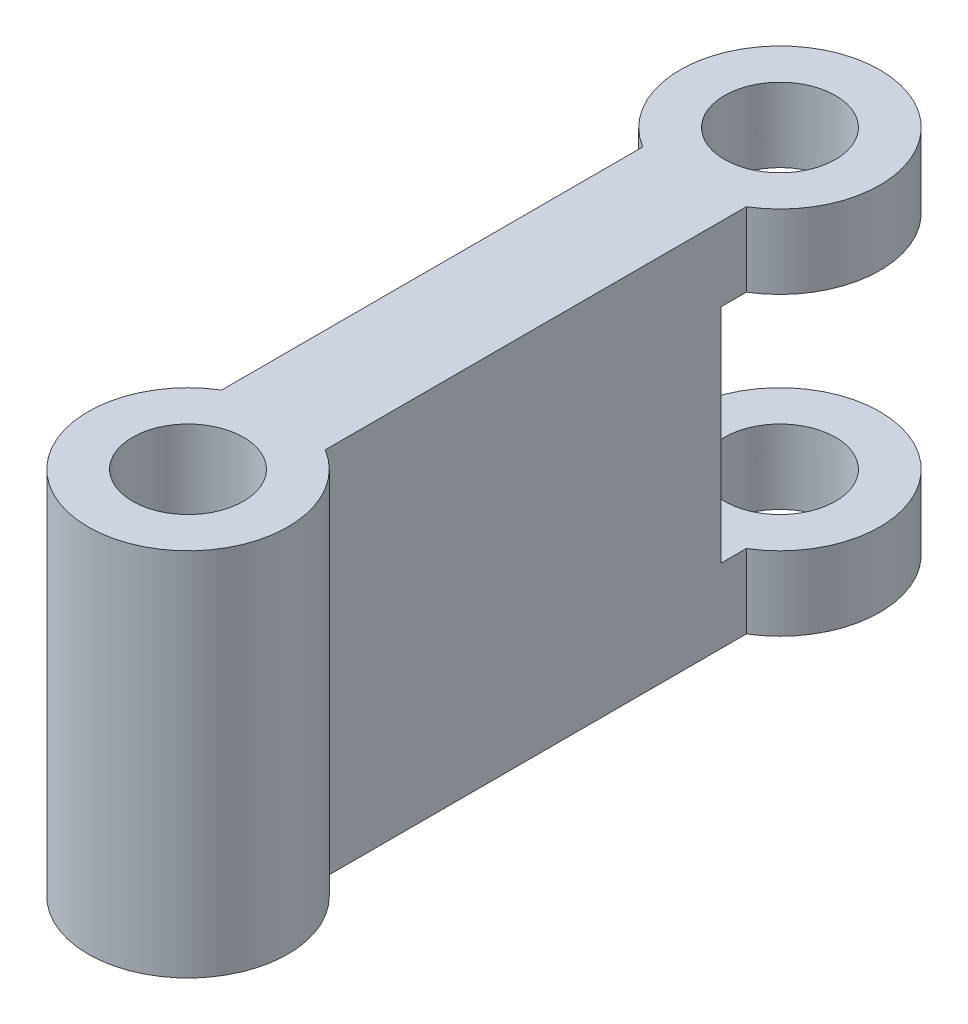
SolidWorks part; units mm, degrees
ref_plane "前视基准面" through (0, 0, 0) normal (0, 0, 1) x (1, 0, 0)
ref_plane "上视基准面" through (0, 0, 0) normal (0, 1, 0) x (1, 0, 0)
ref_plane "右视基准面" through (0, 0, 0) normal (1, 0, 0) x (0, 0, -1)
sketch "草图1" plane through (0, 0, 0) normal (0, 1, 0) x (1, 0, 0)
  line L0 (0, 0) -> (0, -16) construction
  line L3 (-1.4, -2.3087) -> (-1.4, -13.6913)
  line L5 (1.4, -2.3087) -> (1.4, -13.6913)
  circle A0 centre (0, 0) radius 1.5
  circle A1 centre (0, -16) radius 1.5
  arc A2 (1.4, -2.3087) -> (-1.4, -2.3087) centre (0, 0) ccw
  arc A3 (-1.4, -13.6913) -> (1.4, -13.6913) centre (0, -16) ccw
  dimension "D1" = 16
  dimension "D2" = 3
  dimension "D3" = 5.4
  dimension "D4" = 2.8
extrude "凸台-拉伸1" add sketch "草图1" along normal blind 10
ref_plane "基准面1" through (0, 5, 0) normal (0, -1, 0) x (-1, 0, 0)
sketch "草图2" plane through (0, 5, 0) normal (0, -1, 0) x (-1, 0, 0)
  line L0 (-1.4, -3) -> (1.4, -3)
  line L2 (-1.4, -13.6913) -> (-1.4, -2.3087) construction
  line L4 (1.4, -2.3087) -> (1.4, -13.6913) construction
  line L5 (1.4, -3) -> (1.4, -2.3087)
  line L6 (-1.4, -3) -> (-1.4, -2.3087)
  circle A0 centre (0, 0) radius 2.7
  arc A2 (1.4, -2.3087) -> (-1.4, -2.3087) centre (0, 0) ccw construction
  dimension "D1" = 3
extrude "切除-拉伸1" cut sketch "草图2" against normal blind 3 and the other way blind 3
